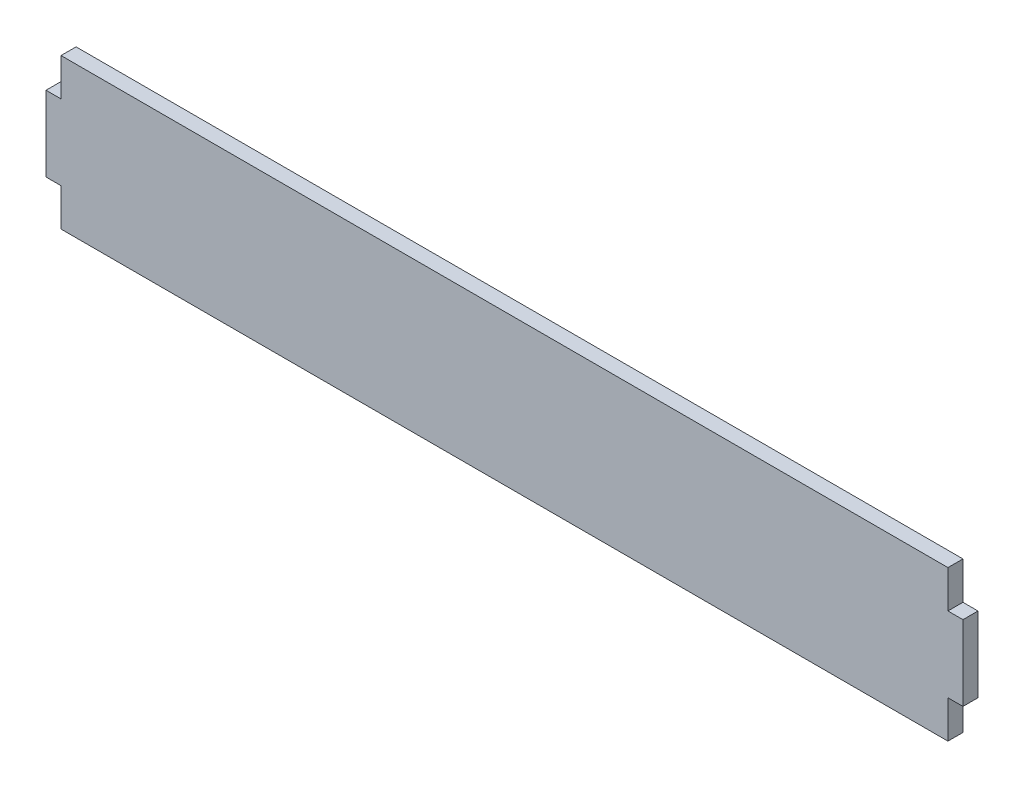
SolidWorks part; units mm, degrees
ref_plane "Front Plane" through (0, 0, 0) normal (0, 0, 1) x (1, 0, 0)
ref_plane "Top Plane" through (0, 0, 0) normal (0, 1, 0) x (1, 0, 0)
ref_plane "Right Plane" through (0, 0, 0) normal (1, 0, 0) x (0, 0, -1)
sketch "Sketch1" plane through (0, 0, 0) normal (0, 0, 1) x (1, 0, 0)
  line L0 (-147.5, 0) -> (-147.5, 46.7481) construction
  line L1 (0, 0) -> (-295, 0)
  line L2 (0, 0) -> (0, -50)
  line L3 (0, -50) -> (-295, -50)
  line L4 (-295, 0) -> (-295, -50)
  line L5 (0, -37.5) -> (5, -37.5)
  line L6 (0, -37.5) -> (0, -12.5)
  line L7 (0, -12.5) -> (5, -12.5)
  line L8 (5, -37.5) -> (5, -12.5)
  line L9 (-295, -12.5) -> (-300, -12.5)
  line L10 (-300, -37.5) -> (-300, -12.5)
  line L11 (-295, -37.5) -> (-300, -37.5)
  line L12 (-295, -37.5) -> (-295, -12.5)
  point P9 (5, -25)
  dimension "D1" = 295
  dimension "D2" = 50
  dimension "D3" = 5
  dimension "D4" = 25
  dimension "D5" = 25
extrude "Boss-Extrude1" add sketch "Sketch1" along normal blind 5 contours L1 L4 L3 L2 | L5 L8 L7 L2 | L11 L4 L9 L10
